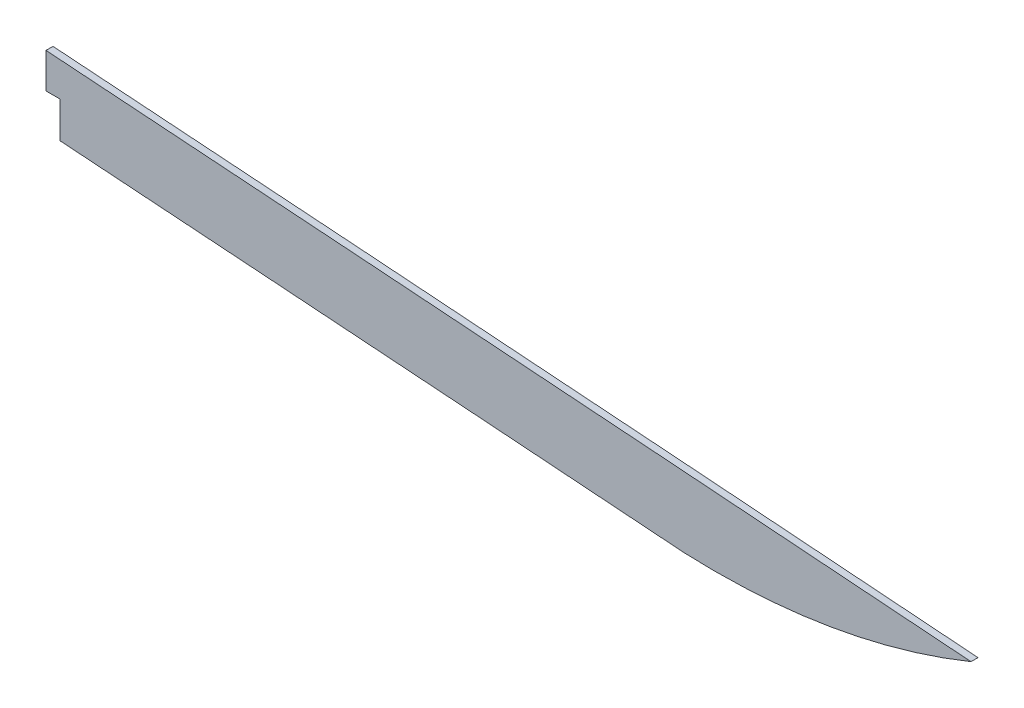
SolidWorks part; units mm, degrees
ref_plane "Front Plane" through (0, 0, 0) normal (0, 0, 1) x (1, 0, 0)
ref_plane "Top Plane" through (0, 0, 0) normal (0, 1, 0) x (1, 0, 0)
ref_plane "Right Plane" through (0, 0, 0) normal (1, 0, 0) x (0, 0, -1)
sketch "Sketch1" plane through (0, 0, 0) normal (0, 0, 1) x (1, 0, 0)
  line L0 (0, 0) -> (0, -50.1218)
  line L2 (0, -50.1218) -> (20, -50.1218)
  line L5 (20, -50.1218) -> (20, -101.6418)
  arc A0 (1319.078, -95.3983) -> (0, 0) centre (-18662.1606, -267209.9818) ccw
  arc A1 (911.0805, -165.4599) -> (20, -101.6418) centre (-18662.1606, -267209.9818) ccw
  arc A3 (1311.6184, -195.1197) -> (-6.9671, -99.757) centre (-18662.1606, -267209.9818) ccw construction
  spline S0 degree 2 poles (1319.078, -95.3983) (1125.1241, -174.1902) (911.0805, -165.4599) knots 0 0 0 1 1 1
  dimension "D1" = 100
extrude "Boss-Extrude1" add sketch "Sketch1" along normal blind 10
